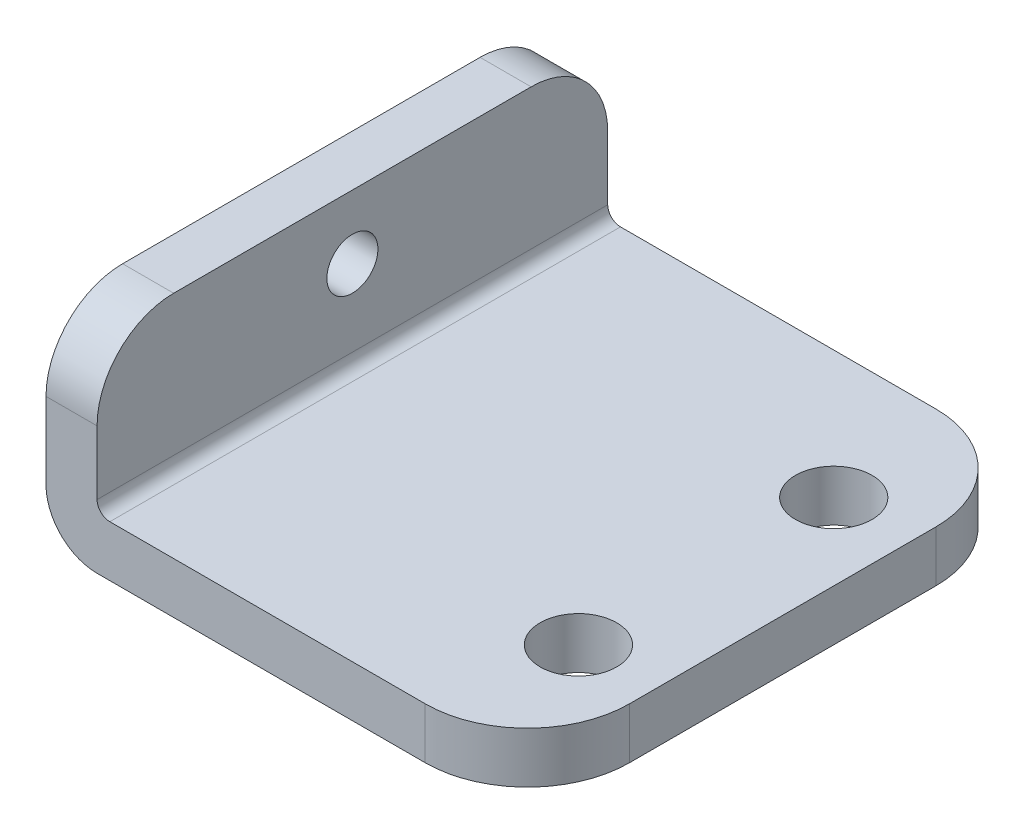
SolidWorks part; units mm, degrees
ref_plane "Front Plane" through (0, 0, 0) normal (0, 0, 1) x (1, 0, 0)
ref_plane "Top Plane" through (0, 0, 0) normal (0, 1, 0) x (1, 0, 0)
ref_plane "Right Plane" through (0, 0, 0) normal (1, 0, 0) x (0, 0, -1)
sketch "Sketch1" plane through (0, 0, 0) normal (0, 1, 0) x (1, 0, 0)
  line L1 (-8.4264, -10) -> (8.4264, -10)
  line L2 (-8.4264, -10) -> (-8.4264, 10)
  line L3 (-8.4264, 10) -> (8.4264, 10)
  line L4 (8.4264, -10) -> (8.4264, 10)
  line L5 (-8.4264, -10) -> (8.4264, 10) construction
  line L6 (-8.4264, 10) -> (8.4264, -10) construction
  point P0 (0, 0)
  dimension "D1" = 20
extrude "Boss-Extrude1" add sketch "Sketch1" along normal blind 2
fillet "Fillet1" radius 4 2 edges at (8.4264, 1, -10) (8.4264, 1, 10)
sketch "Sketch2" plane through (-8.4264, 0, 0) normal (-1, 0, 0) x (0, 0, 1)
  line L0 (-10, 0) -> (10, 0)
  line L1 (-10, 0) -> (-10, 8)
  line L2 (10, 0) -> (10, 8)
  line L3 (-10, 8) -> (10, 8)
  circle A0 centre (0, 5.5) radius 1
  dimension "D3" = 2
  dimension "D1" = 8
  dimension "D2" = 10
  dimension "D4" = 5.5
extrude "Boss-Extrude2" add sketch "Sketch2" along normal blind 2
fillet "Fillet2" radius 3 1 edges at (-9.4264, 8, 10)
fillet "Fillet3" radius 3 1 edges at (-9.4264, 8, -10)
fillet "Fillet4" radius 2 1 edges at (-10.4264, 0, 0)
fillet "Fillet5" radius 0.5 1 edges at (-8.4264, 2, 0)
sketch "Sketch3" plane through (0, 2, 0) normal (0, 1, 0) x (1, 0, 0)
  line L0 (-7.9264, -10) -> (4.4264, -10) construction
  line L1 (4.4264, 10) -> (-7.9264, 10) construction
  line L2 (8.4264, -6) -> (8.4264, 6) construction
  circle A0 centre (5.4264, 5) radius 1.5
  circle A1 centre (5.4264, -5) radius 1.5
  dimension "D2" = 3
  dimension "D3" = 3
  dimension "D1" = 10
  dimension "D4" = 5
  dimension "D5" = 5
  dimension "D6" = 3
extrude "Cut-Extrude1" cut sketch "Sketch3" against normal through all
